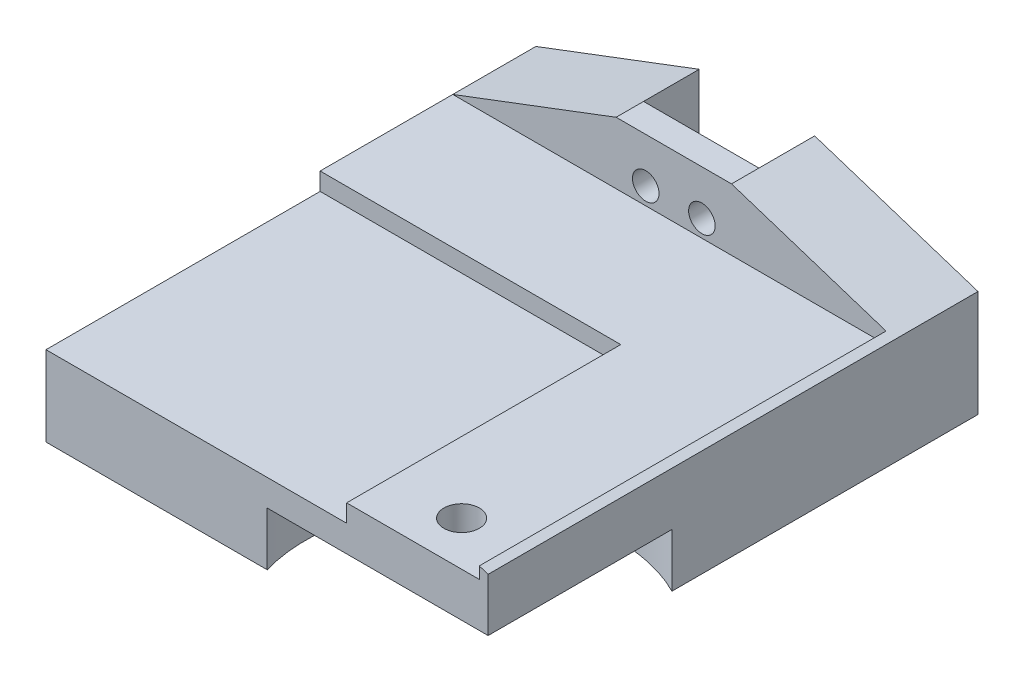
SolidWorks part; units mm, degrees
ref_plane "Front Plane" through (0, 0, 0) normal (0, 0, 1) x (1, 0, 0)
ref_plane "Top Plane" through (0, 0, 0) normal (0, 1, 0) x (1, 0, 0)
ref_plane "Right Plane" through (0, 0, 0) normal (1, 0, 0) x (0, 0, -1)
sketch "OutlineSketch2" plane through (0, 0, 0) normal (0, 1, 0) x (1, 0, 0)
  line L1 (0, 0) -> (50, 0)
  line L2 (0, 0) -> (0, 55.4)
  line L3 (0, 55.4) -> (50, 55.4)
  line L4 (50, 0) -> (50, 55.4)
  circle A0 centre (42, 5) radius 2
  dimension "D5" = 4
  dimension "D1" = 5
  dimension "D2" = 8
  dimension "D3" = 50.4
  dimension "D4" = 50
extrude "OutlineBoss-Extrude1" add sketch "OutlineSketch2" along normal blind 18.05
sketch "BuildPlateCutoutSketch1" plane through (0, 18.05, 0) normal (0, 1, 0) x (1, 0, 0)
  line L1 (0, 0) -> (49, 0)
  line L2 (0, 0) -> (0, 46)
  line L3 (0, 46) -> (49, 46)
  line L4 (49, 0) -> (49, 46)
  dimension "D1" = 7
  dimension "D2" = 41
extrude "BuildPlateCutoutCut-Extrude7" cut sketch "BuildPlateCutoutSketch1" against normal blind 7
sketch "MicroSwitchSketch9" plane through (0, 0, -55.4) normal (0, 0, -1) x (-1, 0, 0)
  line L0 (-50, 18.05) -> (0, 18.05) construction
  line L1 (-31.525, 18.05) -> (-18.475, 18.05)
  line L2 (-31.525, 18.05) -> (-31.525, 6)
  line L3 (-31.525, 6) -> (-18.475, 6)
  line L4 (-18.475, 18.05) -> (-18.475, 6)
  line L6 (0, 18.05) -> (0, 0) construction
  dimension "D1" = 13.05
  dimension "D2" = 12.05
  dimension "D3" = 18.475
extrude "MicroSwitchCut-Extrude6" cut sketch "MicroSwitchSketch9" against normal blind 6.3
sketch "MicroSwitchMountingHolesSketch10" plane through (0, 0, -49.1) normal (0, 0, -1) x (-1, 0, 0)
  line L3 (-31.525, 18.05) -> (-31.525, 6) construction
  line L4 (-18.475, 6) -> (-18.475, 18.05) construction
  line L6 (-31.525, 6) -> (-18.475, 6) construction
  circle A0 centre (-28.175, 13) radius 1.5
  circle A1 centre (-21.825, 13) radius 1.5
  dimension "D1" = 3
  dimension "D2" = 3.35
  dimension "D3" = 3.35
  dimension "D4" = 7
extrude "MicroSwitchMountingHolesCut-Extrude4" cut sketch "MicroSwitchMountingHolesSketch10" against normal blind 3.1
sketch "CableCutSketch11" plane through (0, 6, 0) normal (0, 1, 0) x (1, 0, 0)
  line L0 (24.125, 55.4) -> (24.125, 53.65)
  line L2 (24.125, 53.65) -> (23.125, 53.65)
  line L3 (23.125, 53.65) -> (23.125, 51.9)
  line L4 (23.125, 51.9) -> (26.875, 51.9)
  line L5 (26.875, 51.9) -> (26.875, 53.65)
  line L6 (26.875, 53.65) -> (25.875, 53.65)
  line L7 (25.875, 53.65) -> (25.875, 55.4)
  line L8 (25.875, 55.4) -> (24.125, 55.4)
  line L11 (31.525, 55.4) -> (18.475, 55.4) construction
  line L12 (31.525, 49.1) -> (31.525, 55.4) construction
  dimension "D1" = 1.75
  dimension "D2" = 3.75
  dimension "D3" = 1.75
  dimension "D4" = 4.65
extrude "CableCutCut-Extrude5" cut sketch "CableCutSketch11" against normal through all
sketch "HeatMatCutSketch3" plane through (0, 11.05, 0) normal (0, 1, 0) x (1, 0, 0)
  line L0 (0, 0) -> (49, 0) construction
  line L1 (0, 0) -> (34, 0)
  line L2 (0, 0) -> (0, 31)
  line L3 (0, 31) -> (34, 31)
  line L4 (34, 0) -> (34, 31)
  line L5 (0, 46) -> (0, 0) construction
  line L6 (49, 46) -> (0, 46) construction
  line L7 (49, 0) -> (49, 46) construction
  dimension "D1" = 15
  dimension "D2" = 15
extrude "HeatMatCut-Extrude8" cut sketch "HeatMatCutSketch3" against normal blind 2
sketch "BallJointCutoutSketch4" plane through (0, 0, 0) normal (0, -1, 0) x (1, 0, 0)
  line L0 (25.0209, 0) -> (50, 0)
  line L2 (50, 0) -> (50, -20.7889)
  line L4 (50, 0) -> (50, -55.4) construction
  arc A0 (25.0209, 0) -> (50, -20.7889) centre (42, -5) ccw
  dimension "D1" = 35.4
extrude "BallJointCut-Extrude9" cut sketch "BallJointCutoutSketch4" against normal blind 6.05
chamfer "Chamfer1" distance 7 distance2 18.475 1 edges at (0, 18.05, -50.7)
chamfer "Chamfer2" distance 6 distance2 18.475 1 edges at (50, 18.05, -27.7)
equation "\"BuildPlateStandoffHolesDistanceFromLeftOrRightSide\"= 7mm"
equation "\"BuildPlateStandoffHolesDistanceFromBackSide\"= 41mm"
equation "\"BedSpringHoleSize\"= \"M4HoleDiameter\""
equation "\"D5@OutlineSketch2\" = \"BedSpringHoleSize\""
equation "\"D1@OutlineBoss-Extrude1\" = \"BuildPlateZEndstopDepth\""
equation "\"BuildPlateStandoffHolesDistanceFromFront\"= 7mm"
equation "\"M4HoleDiameter\"= 4mm"
equation "\"D1@OutlineSketch2\"=\"RightedgeSize\"+ \"BedSpringHoleSize\""
equation "\"D2@OutlineSketch2\"=  \"BuildPlateStandoffHolesDistanceFromFront\" + \"RightedgeSize\""
equation "\"D3@OutlineSketch2\" = \"BuildPlateStandoffHolesDistanceFromBackSide\" + \"BackEdgeSize\""
equation "\"RightedgeSize\"= 1mm"
equation "\"MicroSwitchLength\" = 13.05mm"
equation "\"MicroSwitchHeight\"= 6.55mm"
equation "\"MicroSwitchHoleOffsetFromSide\"= 3.35mm"
equation "\"MicroSwutchTerminalHeight\"= 3.5mm"
equation "\"MicroSwitchExtraMountingHeight\"= 2mm"
equation "\"MicroSwitchDepth\"= 2.8mm"
equation "\"BuildPlateZEndstopDepth\"= \"BuildPlateDepth\" + \"MicroSwutchTerminalHeight\" + \"MicroSwitchHeight\""
equation "\"BackEdgeSize\"= \"EndStopCableDepth\" * 2 + \"MicroSwitchDepth\" + \"M2HeatInsertHoleDepth\""
equation "\"MicroSwitchHoleOffsetFromBottom\"= 7mm"
equation "\"M2HeatInsertHoleDiameter\"= 3mm'Spec"
equation "\"M2HeatInsertHoleDepth\"= 3.1mm'Spec"
equation "\"BuildPlateEndStopHolderWidth\"= 50mm"
equation "\"D4@OutlineSketch2\"=\"BuildPlateEndStopHolderWidth\""
equation "\"D1@MicroSwitchSketch9\" = \"MicroSwitchLength\""
equation "\"D1@MicroSwitchMountingHolesSketch10\" = \"M2HeatInsertHoleDiameter\""
equation "\"D1@MicroSwitchMountingHolesCut-Extrude4\" = \"M2HeatInsertHoleDepth\""
equation "\"EndStopCableWidth\"=3.75"
equation "\"D2@CableCutSketch11\" = \"EndStopCableWidth\""
equation "\"EndStopCableDepth\"=1.75"
equation "\"D1@CableCutSketch11\" = \"EndStopCableDepth\""
equation "\"D3@CableCutSketch11\" = \"EndStopCableDepth\""
equation "\"BuildPlateDepth\"= 8mm'Spec"
equation "\"D1@MicroSwitchCut-Extrude6\"=\"BackEdgeSize\" - \"M2HeatInsertHoleDepth\""
equation "\"D2@MicroSwitchMountingHolesSketch10\"=\"MicroSwitchHoleOffsetFromSide\""
equation "\"D3@MicroSwitchMountingHolesSketch10\"=\"MicroSwitchHoleOffsetFromSide\""
equation "\"D4@MicroSwitchMountingHolesSketch10\"=\"MicroSwitchHoleOffsetFromBottom\""
equation "\"D1@BuildPlateCutoutSketch1\" = \"BuildPlateStandoffHolesDistanceFromLeftOrRightSide\""
equation "\"D2@BuildPlateCutoutSketch1\" = \"BuildPlateStandoffHolesDistanceFromBackSide\""
equation "\"D1@BuildPlateCutoutCut-Extrude7\"=\"BuildPlateDepth\"-1mm"
equation "\"D2@MicroSwitchSketch9\"=\"MicroSwitchExtraMountingHeight\"+ \"MicroSwutchTerminalHeight\" + \"MicroSwitchHeight\""
equation "\"BallJointDiameter\"= 1in"
equation "\"D1@BallJointCut-Extrude9\"=\"BuildPlateZEndstopDepth\" - \"BuildPlateDepth\" -1mm - 3mm"
equation "\"D1@Chamfer1\"=7"
equation "\"D3@Chamfer1\"=(\"BuildPlateEndStopHolderWidth\"-\"MicroSwitchLength\")/2"
equation "\"D3@Chamfer2\"=(\"BuildPlateEndStopHolderWidth\"-\"MicroSwitchLength\")/2"
equation "\"D3@MicroSwitchSketch9\"=(\"BuildPlateEndStopHolderWidth\"-\"MicroSwitchLength\")/2"
equation "\"D4@CableCutSketch11\"=(\"MicroSwitchLength\"-\"EndStopCableWidth\")/2"
equation "\"HeatMatBuildPlateBorderSize\"=15"
equation "\"D1@HeatMatCutSketch3\"=\"HeatMatBuildPlateBorderSize\""
equation "\"D2@HeatMatCutSketch3\"=\"HeatMatBuildPlateBorderSize\""
equation "\"D1@BallJointCutoutSketch4\"=\"BallJointDiameter\" + 10mm"
